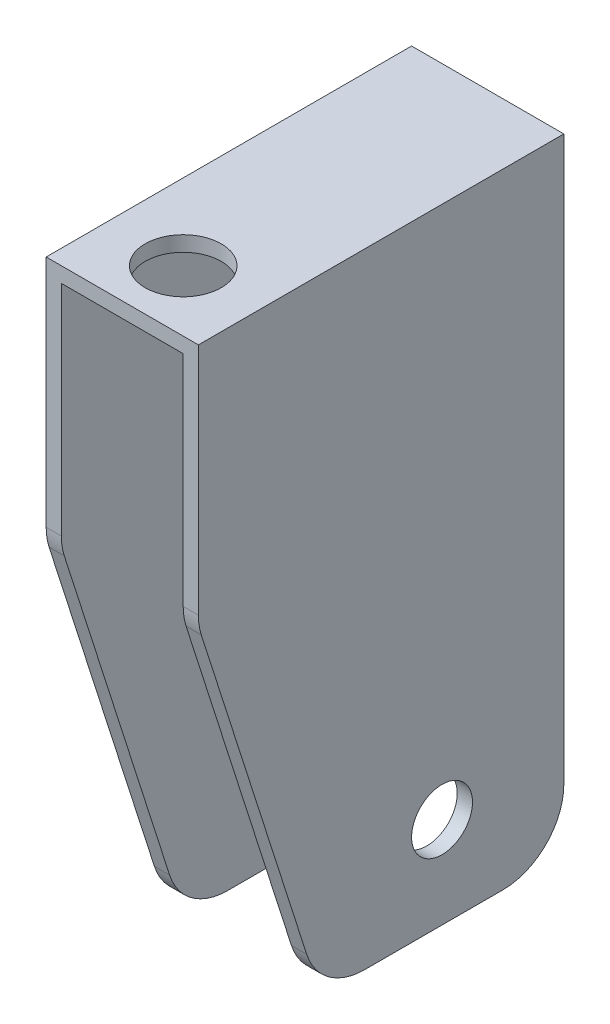
SolidWorks part; units mm, degrees
ref_plane "Plan de face" through (0, 0, 0) normal (0, 0, 1) x (1, 0, 0)
ref_plane "Plan de dessus" through (0, 0, 0) normal (0, 1, 0) x (1, 0, 0)
ref_plane "Plan de droite" through (0, 0, 0) normal (1, 0, 0) x (0, 0, -1)
sketch "Esquisse1" plane through (0, 0, 0) normal (0, 0, 1) x (1, 0, 0)
  line L0 (0, 0) -> (0, 205)
  line L1 (0, 205) -> (50, 205)
  line L2 (25, 205) -> (25, 0) construction
  line L3 (0, 0) -> (5, 0)
  line L4 (5, 0) -> (5, 200)
  line L5 (5, 200) -> (45, 200)
  line L6 (45, 0) -> (45, 200)
  line L7 (50, 0) -> (45, 0)
  line L8 (50, 0) -> (50, 205)
  point P9 (25, 200)
  dimension "D1" = 5
  dimension "D2" = 5
  dimension "D3" = 200
  dimension "D4" = 40
extrude "Boss.-Extru.1" add sketch "Esquisse1" along normal blind 120
sketch "Esquisse2" plane through (50, 0, 0) normal (1, 0, 0) x (0, 0, -1)
  line L0 (-80, 0) -> (-120, 125)
  line L1 (-120, 0) -> (0, 0) construction
  line L2 (-120, 0) -> (-120, 205) construction
  line L3 (-120, 125) -> (-120, 0)
  line L4 (-120, 0) -> (-80, 0)
  line L5 (-120, 205) -> (0, 205) construction
  dimension "D1" = 80
  dimension "D2" = 80
extrude "Enlèv. mat.-Extru.1" cut sketch "Esquisse2" against normal through all both and the other way through all
sketch "Esquisse3" plane through (50, 0, 0) normal (1, 0, 0) x (0, 0, -1)
  line L0 (-40, 0) -> (-40, 30) construction
  line L1 (-80, 0) -> (0, 0) construction
  circle A0 centre (-40, 30) radius 10
  dimension "D1" = 20
  dimension "D2" = 30
extrude "Enlèv. mat.-Extru.2" cut sketch "Esquisse3" against normal through all both and the other way through all
fillet "Congé1" radius 20 6 edges at (2.5, 0, 80) (47.5, 0, 80) (2.5, 0, 0) (47.5, 0, 0)
sketch "Esquisse4" plane through (0, 205, 0) normal (0, 1, 0) x (1, 0, 0)
  line L0 (25, 0) -> (25, -100) construction
  line L1 (50, 0) -> (0, 0) construction
  circle A0 centre (25, -100) radius 12.5
  dimension "D1" = 25
  dimension "D2" = 100
extrude "Enlèv. mat.-Extru.3" cut sketch "Esquisse4" against normal up to next
